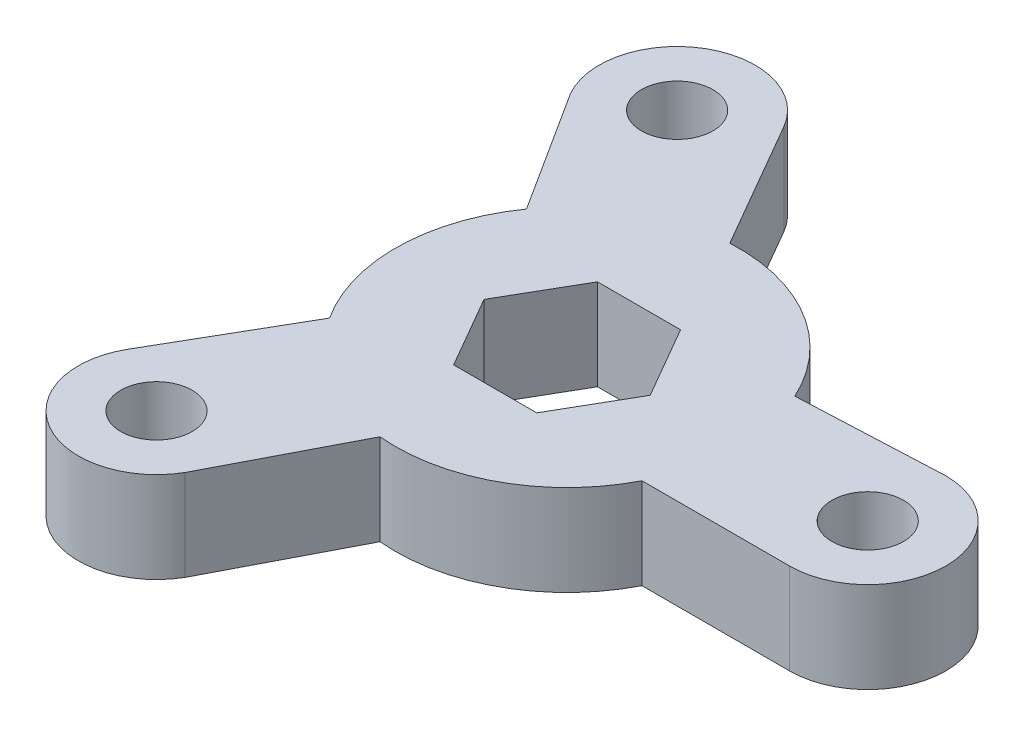
SolidWorks part; units mm, degrees
ref_plane "Front" through (0, 0, 0) normal (0, 0, 1) x (1, 0, 0)
ref_plane "Top" through (0, 0, 0) normal (0, 1, 0) x (1, 0, 0)
ref_plane "Right" through (0, 0, 0) normal (1, 0, 0) x (0, 0, -1)
sketch "Sketch1" plane through (0, 0, 0) normal (0, 1, 0) x (1, 0, 0)
  line L0 (2.5148, 0.2447) -> (13.0148, 0.2447)
  line L1 (2.5148, 0.2447) -> (-2.7352, 9.338)
  line L2 (2.5148, 0.2447) -> (-2.7352, -8.8486)
  line L3 (2.5148, 0.2447) -> (-2.7352, 9.338) construction
  line L10 (2.5148, 0.2447) -> (13.0148, 0.2447) construction
  line L11 (13.0148, -2.4841) -> (7.8583, -2.4841)
  line L12 (13.0148, 2.9736) -> (7.9691, 2.7447)
  line L13 (-5.0985, -7.4841) -> (-2.5203, -3.0185)
  line L14 (-0.372, -10.213) -> (1.9526, -5.7289)
  line L15 (-0.372, 10.7024) -> (2.2062, 6.2368)
  line L16 (-5.0985, 7.9736) -> (-2.3775, 3.7183)
  line L18 (5.4159, 0.2447) -> (3.9654, 2.7572)
  line L19 (3.9654, 2.7572) -> (1.0642, 2.7572)
  line L20 (1.0642, 2.7572) -> (-0.3864, 0.2447)
  line L21 (-0.3864, 0.2447) -> (1.0642, -2.2678)
  line L22 (1.0642, -2.2678) -> (3.9654, -2.2678)
  line L23 (3.9654, -2.2678) -> (5.4159, 0.2447)
  circle A0 centre (-2.7352, 9.338) radius 1.25
  circle A1 centre (13.0148, 0.2447) radius 1.25
  circle A2 centre (-2.7352, -8.8486) radius 1.25
  circle A3 centre (2.5148, 0.2447) radius 2.5125 construction
  arc A4 (-0.372, 10.7024) -> (-5.0985, 7.9736) centre (-2.7352, 9.338) ccw
  circle A5 centre (2.5148, 0.2447) radius 6
  arc A6 (13.0148, -2.4841) -> (13.0148, 2.9736) centre (13.0148, 0.2447) ccw
  arc A7 (-5.0985, -7.4841) -> (-0.372, -10.213) centre (-2.7352, -8.8486) ccw
  point P8 (-37.6157, 20.9061)
  point P39 (2.5148, 0.2447)
  dimension "D1" = 3
  dimension "D2" = 120
  dimension "D3" = 3
extrude "Boss-Extrude1" add sketch "Sketch1" along normal blind 3.175
